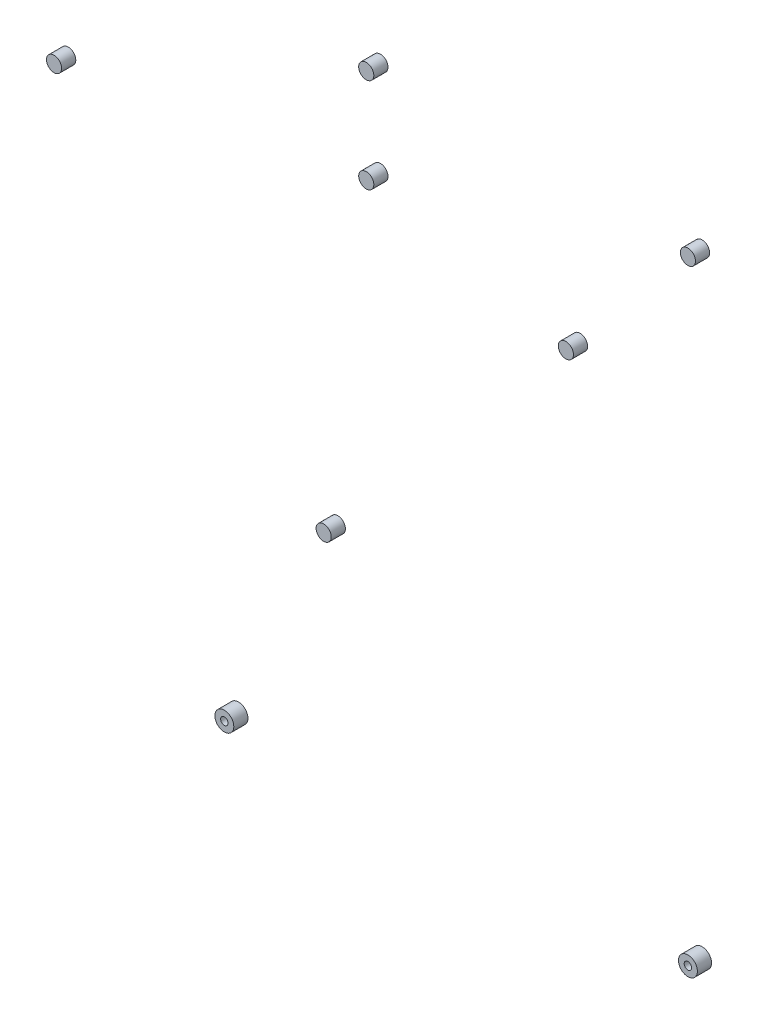
SolidWorks part; units mm, degrees
ref_plane "Front Plane" through (0, 0, 0) normal (0, 0, 1) x (1, 0, 0)
ref_plane "Top Plane" through (0, 0, 0) normal (0, 1, 0) x (1, 0, 0)
ref_plane "Right Plane" through (0, 0, 0) normal (1, 0, 0) x (0, 0, -1)
sketch "Sketch1" plane through (0, 0, 0) normal (0, 0, 1) x (1, 0, 0)
  circle A17 centre (96.52, -79.756) radius 2.54
  circle A18 centre (-27.94, -85.09) radius 2.54
  circle A19 centre (-1.27, -27.94) radius 2.032
  circle A20 centre (63.754, 46.99) radius 2.032
  circle A21 centre (10.16, 59.69) radius 2.032
  circle A22 centre (10.16, 85.09) radius 2.032
  circle A23 centre (96.52, 85.09) radius 2.032
  circle A24 centre (-73.66, 44.831) radius 2.032
  circle A25 centre (96.52, -79.756) radius 1.397 construction
  circle A26 centre (96.52, -79.756) radius 1
  circle A27 centre (-27.94, -85.09) radius 1
  circle A28 centre (-27.94, -85.09) radius 1.397 construction
  dimension "D1" = 5.08
  dimension "D2" = 4.064
  dimension "D3" = 5.08
  dimension "D4" = 4.064
  dimension "D5" = 4.064
  dimension "D6" = 4.064
  dimension "D7" = 4.064
  dimension "D8" = 4.064
  dimension "D9" = 2
  dimension "D10" = 2
extrude "Boss-Extrude1" add sketch "Sketch1" along normal blind 3.81
